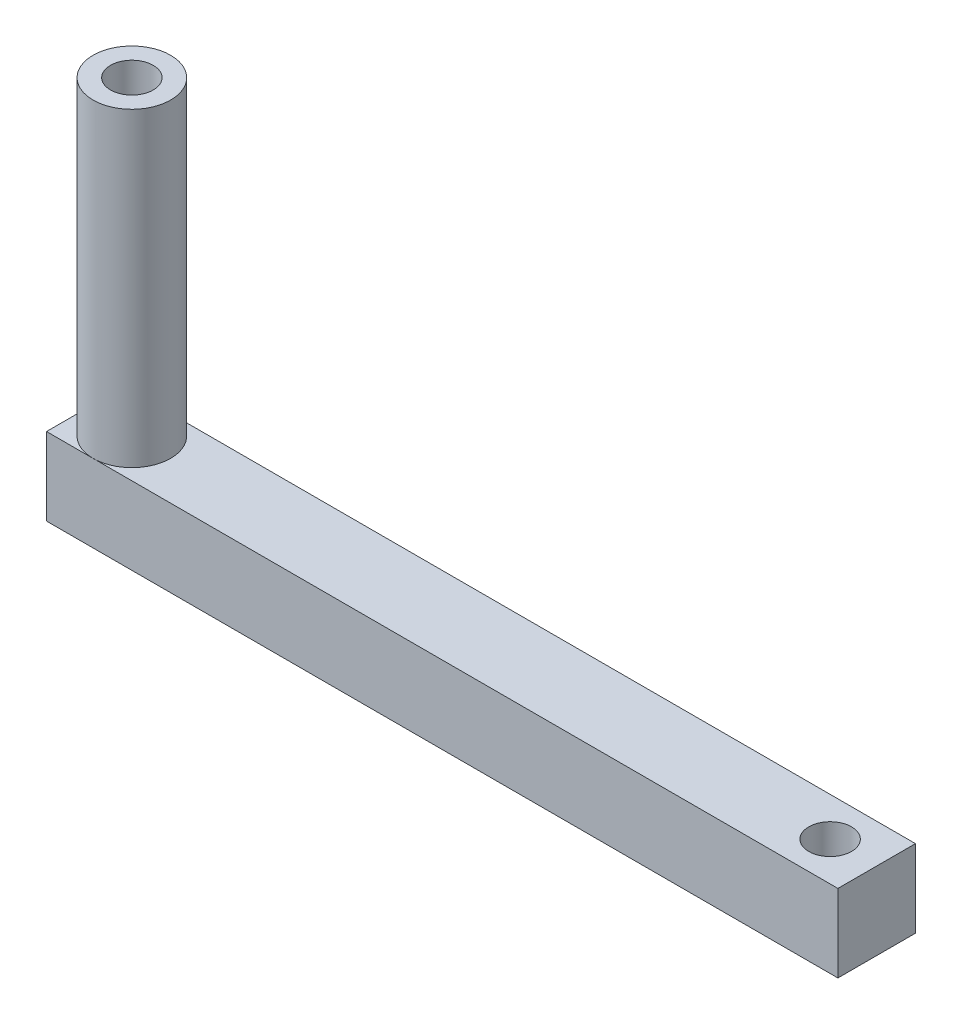
SolidWorks part; units mm, degrees
ref_plane "Front Plane" through (0, 0, 0) normal (0, 0, 1) x (1, 0, 0)
ref_plane "Top Plane" through (0, 0, 0) normal (0, 1, 0) x (1, 0, 0)
ref_plane "Right Plane" through (0, 0, 0) normal (1, 0, 0) x (0, 0, -1)
sketch "Sketch1" plane through (0, 0, 0) normal (0, 1, 0) x (1, 0, 0)
  line L1 (0, 0) -> (64.77, 0)
  line L2 (0, 0) -> (0, 6.35)
  line L3 (0, 6.35) -> (64.77, 6.35)
  line L4 (64.77, 0) -> (64.77, 6.35)
  circle A0 centre (3.81, 3.175) radius 1.75
  circle A1 centre (60.96, 3.175) radius 1.75
  dimension "D1" = 3.5
  dimension "D2" = 57.15
  dimension "D3" = 3.81
  dimension "D4" = 3.81
  dimension "D5" = 6.35
  dimension "D6" = 3.175
extrude "Boss-Extrude1" add sketch "Sketch1" against normal blind 6.35
sketch "Sketch2" plane through (0, -6.35, 0) normal (0, -1, 0) x (1, 0, 0)
  line L1 (0, 0) -> (64.77, 0) construction
  circle A0 centre (3.81, -3.175) radius 3.175
  circle A1 centre (3.81, -3.175) radius 1.75
  circle A2 centre (3.81, -3.175) radius 1.75 construction
extrude "Boss-Extrude2" add sketch "Sketch2" against normal blind 25.4 from offset 6.35
